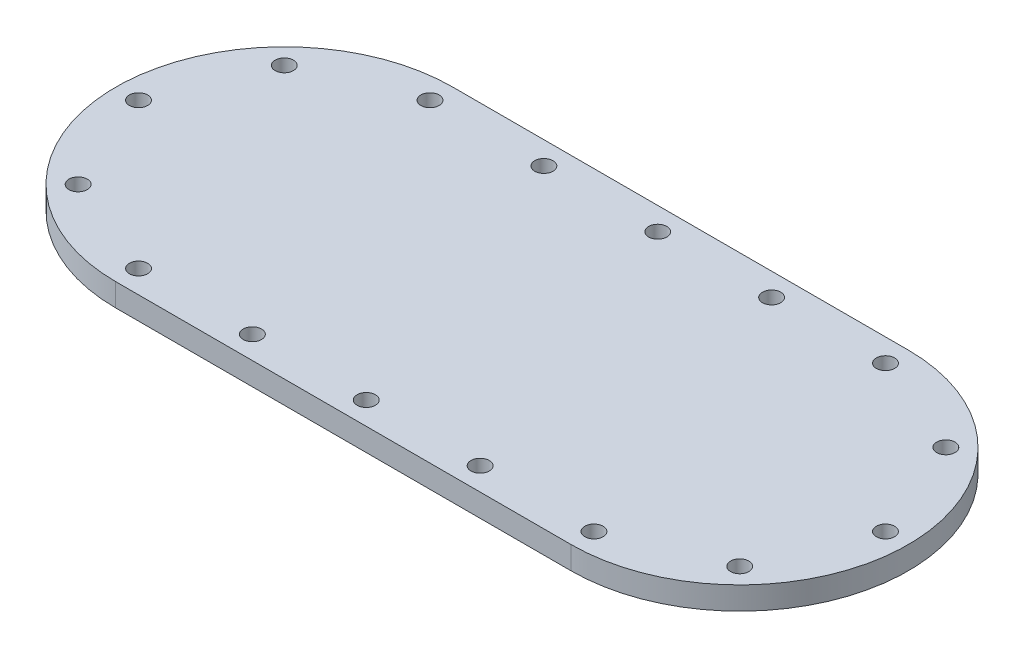
SolidWorks part; units mm, degrees
material "McMaster Ultra-Scratch-Resistant Cast Acrylic"
ref_plane "Front Plane" through (0, 0, 0) normal (0, 0, 1) x (1, 0, 0)
ref_plane "Top Plane" through (0, 0, 0) normal (0, 1, 0) x (1, 0, 0)
ref_plane "Right Plane" through (0, 0, 0) normal (1, 0, 0) x (0, 0, -1)
sketch "Sketch1" plane through (0, 0, 0) normal (0, 1, 0) x (1, 0, 0)
  line L0 (0, 46.99) -> (0, -46.99) construction
  line L3 (-63.5, 46.99) -> (63.5, 46.99)
  line L4 (-63.5, -46.99) -> (63.5, -46.99)
  line L5 (-63.5, 40.64) -> (63.5, 40.64) construction
  line L6 (-63.5, -40.64) -> (63.5, -40.64) construction
  arc A2 (63.5, -46.99) -> (63.5, 46.99) centre (63.5, 0) ccw
  arc A3 (-63.5, 46.99) -> (-63.5, -46.99) centre (-63.5, 0) ccw
  arc A4 (63.5, -40.64) -> (63.5, 40.64) centre (63.5, 0) ccw construction
  arc A5 (-63.5, 40.64) -> (-63.5, -40.64) centre (-63.5, 0) ccw construction
  circle A6 centre (-63.5, 40.64) radius 2.5527
  circle A7 centre (-31.75, 40.64) radius 2.5527
  circle A8 centre (0, 40.64) radius 2.5527
  circle A9 centre (31.75, 40.64) radius 2.5527
  circle A10 centre (63.5, 40.64) radius 2.5527
  circle A23 centre (92.2368, 28.7368) radius 2.5527
  circle A24 centre (104.14, 0) radius 2.5527
  circle A25 centre (92.2368, -28.7368) radius 2.5527
  circle A26 centre (63.5, -40.64) radius 2.5527
  circle A27 centre (-92.2368, 28.7368) radius 2.5527
  circle A28 centre (-104.14, 0) radius 2.5527
  circle A29 centre (-92.2368, -28.7368) radius 2.5527
  circle A30 centre (-63.5, -40.64) radius 2.5527
  circle A31 centre (31.75, -40.64) radius 2.5527
  circle A32 centre (0, -40.64) radius 2.5527
  circle A33 centre (-31.75, -40.64) radius 2.5527
  arc A34 (63.5, -40.64) -> (63.5, 40.64) centre (63.5, 0) ccw construction
  arc A35 (-63.5, 40.64) -> (-63.5, -40.64) centre (-63.5, 0) ccw construction
  point P42 (-63.5, 0)
  point P51 (-63.5, 0)
  point P53 (63.5, 0)
  dimension "D4" = 5
  dimension "1/4 - 20 bolt clearance" = 5.1054
  dimension "D5" = 5
  dimension "D1" = 127
  dimension "D2" = 93.98
  dimension "D3" = 6.35
  dimension "D7" = 4
  dimension "D6" = 5
extrude "Boss-Extrude1" add sketch "Sketch1" along normal blind 6.35
sketch "Sketch2" plane through (0, 0, 0) normal (0, -1, 0) x (1, 0, 0)
  line L0 (1.3877, 29.693) -> (65.9877, 29.693) construction
  line L1 (65.9877, 34.0618) -> (1.3877, 34.0618) construction
  line L2 (65.9877, -29.4382) -> (-63.2123, -29.4382) construction
  line L3 (-63.2123, -33.807) -> (65.9877, -33.807) construction
  line L4 (-63.2123, 29.693) -> (1.3877, 29.693) construction
  line L5 (1.3877, 34.0618) -> (-63.2123, 34.0618) construction
  line L6 (1.3877, 29.693) -> (65.9877, 29.693) construction
  line L7 (65.9877, 34.0618) -> (1.3877, 34.0618) construction
  line L8 (65.9877, -29.4382) -> (-63.2123, -29.4382) construction
  line L9 (-63.2123, -33.807) -> (65.9877, -33.807) construction
  line L10 (-63.2123, 29.693) -> (1.3877, 29.693) construction
  line L11 (1.3877, 34.0618) -> (-63.2123, 34.0618) construction
  arc A0 (65.9877, -29.4382) -> (65.9877, 29.693) centre (65.9877, 0.1274) ccw construction
  arc A1 (65.9877, -33.807) -> (65.9877, 34.0618) centre (65.9877, 0.1274) ccw construction
  arc A2 (-63.2123, 29.693) -> (-63.2123, -29.4382) centre (-63.2123, 0.1274) ccw construction
  arc A3 (-63.2123, 34.0618) -> (-63.2123, -33.807) centre (-63.2123, 0.1274) ccw construction
  arc A4 (65.9877, -29.4382) -> (65.9877, 29.693) centre (65.9877, 0.1274) ccw construction
  arc A5 (65.9877, -33.807) -> (65.9877, 34.0618) centre (65.9877, 0.1274) ccw construction
  arc A6 (-63.2123, 29.693) -> (-63.2123, -29.4382) centre (-63.2123, 0.1274) ccw construction
  arc A7 (-63.2123, 34.0618) -> (-63.2123, -33.807) centre (-63.2123, 0.1274) ccw construction
